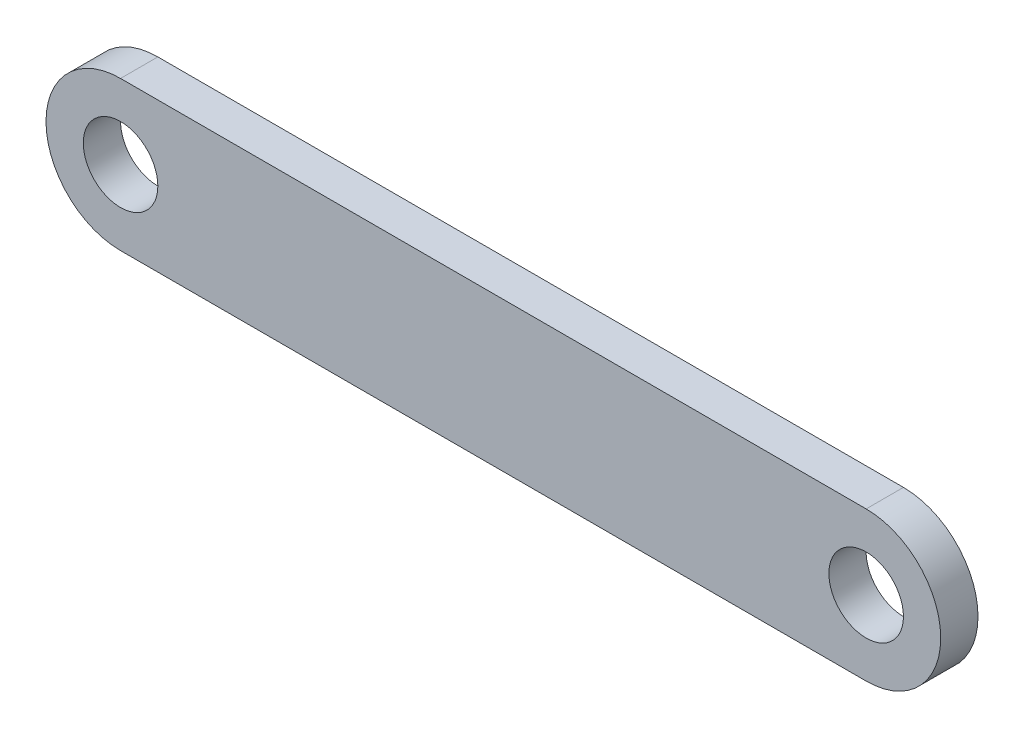
SolidWorks part; units mm, degrees
ref_plane "Ön Düzlem" through (0, 0, 0) normal (0, 0, 1) x (1, 0, 0)
ref_plane "Üst Düzlem" through (0, 0, 0) normal (0, 1, 0) x (1, 0, 0)
ref_plane "Sağ Düzlem" through (0, 0, 0) normal (1, 0, 0) x (0, 0, -1)
sketch "Çizim1" plane through (0, 0, 0) normal (0, 0, 1) x (1, 0, 0)
  line L0 (-38.6982, 2.8866) -> (61.3018, 2.8866) construction
  line L1 (-38.6982, 12.8866) -> (61.3018, 12.8866)
  line L2 (-38.6982, -7.1134) -> (61.3018, -7.1134)
  arc A0 (-38.6982, 12.8866) -> (-38.6982, -7.1134) centre (-38.6982, 2.8866) ccw
  arc A1 (61.3018, -7.1134) -> (61.3018, 12.8866) centre (61.3018, 2.8866) ccw
  circle A2 centre (-38.6982, 2.8866) radius 5
  circle A3 centre (61.3018, 2.8866) radius 5
  point P2 (11.3018, 2.8866)
  dimension "D1" = 100
  dimension "D2" = 20
extrude "Yükseklik-Ekstrüzyon1" add sketch "Çizim1" along normal blind 5
